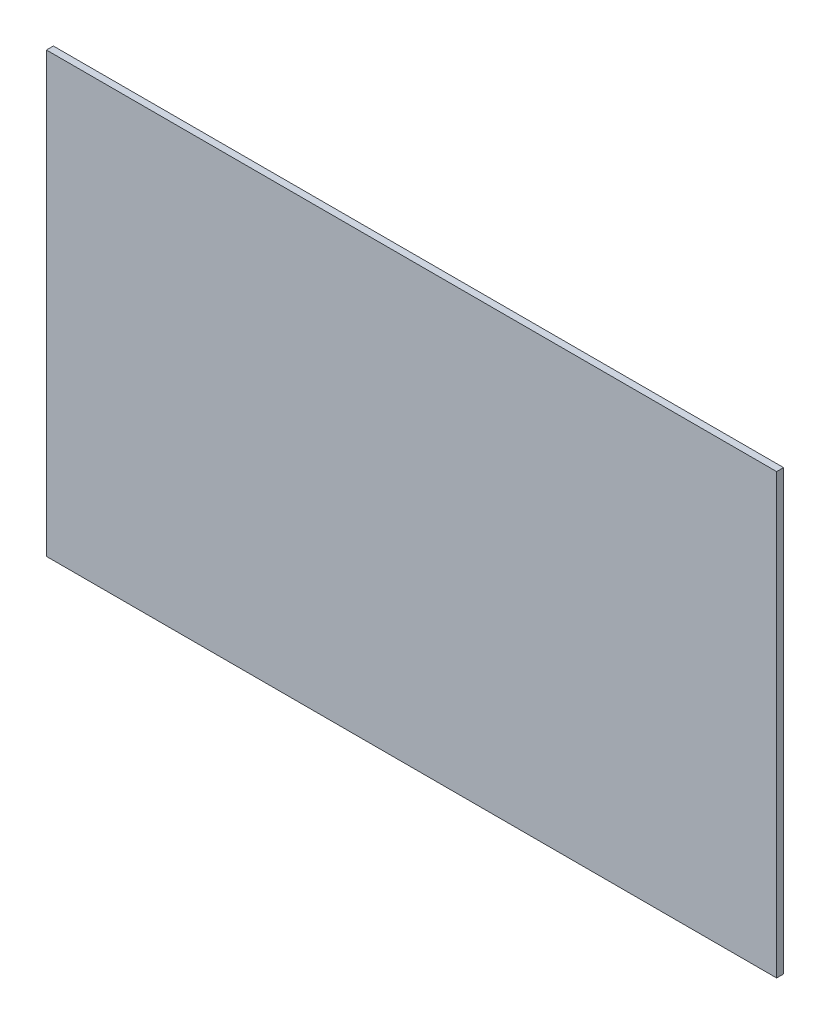
SolidWorks part; units mm, degrees
ref_plane "前基準面" through (0, 0, 0) normal (0, 0, 1) x (1, 0, 0)
ref_plane "上基準面" through (0, 0, 0) normal (0, 1, 0) x (1, 0, 0)
ref_plane "右基準面" through (0, 0, 0) normal (1, 0, 0) x (0, 0, -1)
sketch "草圖1" plane through (0, 0, 0) normal (0, 0, 1) x (1, 0, 0)
  line L1 (-250.4, 150.4) -> (250.4, 150.4)
  line L2 (-250.4, 150.4) -> (-250.4, -150.4)
  line L3 (-250.4, -150.4) -> (250.4, -150.4)
  line L4 (250.4, 150.4) -> (250.4, -150.4)
  line L5 (-250.4, 150.4) -> (250.4, -150.4) construction
  line L6 (-250.4, -150.4) -> (250.4, 150.4) construction
  point P0 (0, 0)
  dimension "D1" = 500.8
  dimension "D2" = 300.8
extrude "填料-伸長1" add sketch "草圖1" along normal blind 4.75 contours L1 L4 L3 L2
